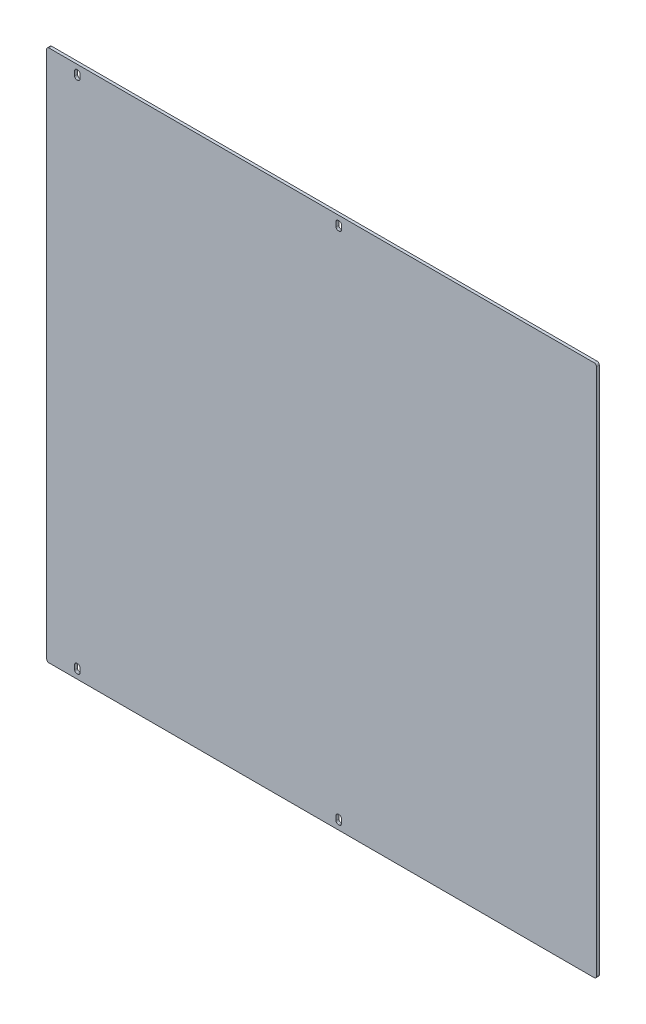
SolidWorks part; units mm, degrees
ref_plane "Front Plane" through (0, 0, 0) normal (0, 0, 1) x (1, 0, 0)
ref_plane "Top Plane" through (0, 0, 0) normal (0, 1, 0) x (1, 0, 0)
ref_plane "Right Plane" through (0, 0, 0) normal (1, 0, 0) x (0, 0, -1)
sketch "Sketch1" plane through (0, 0, 0) normal (0, 0, 1) x (1, 0, 0)
  line L1 (-224.9767, 260.7264) -> (384.6233, 260.7264)
  line L2 (-224.9767, 260.7264) -> (-224.9767, -329.6986)
  line L3 (-224.9767, -329.6986) -> (384.6233, -329.6986)
  line L4 (384.6233, 260.7264) -> (384.6233, -329.6986)
  dimension "D1" = 590.425
  dimension "D2" = 609.6
extrude "Boss-Extrude1" add sketch "Sketch1" along normal blind 3.175 contours L2 L3 L4 L1
fillet "Fillet1" radius 2.54 4 edges at (-224.9767, -329.6986, 1.5875) (384.6233, -329.6986, 1.5875) (384.6233, 260.7264, 1.5875) (-224.9767, 260.7264, 1.5875)
sketch "Sketch2" plane through (0, 0, 3.175) normal (0, 0, 1) x (1, 0, 0)
  line L0 (-190.4767, 245.6044) -> (-191.4767, 245.6044)
  line L1 (-193.9767, 248.1044) -> (-193.9767, 253.1044)
  line L2 (-190.4767, 255.6044) -> (-191.4767, 255.6044)
  line L3 (-187.9767, 248.1044) -> (-187.9767, 253.1044)
  line L4 (-190.9767, 255.6044) -> (-190.9767, 245.6044) construction
  line L5 (-193.9767, 250.6044) -> (-187.9767, 250.6044) construction
  line L6 (-205.9767, 250.6044) -> (403.6233, 250.6044) construction
  line L7 (-205.9767, 605.4044) -> (-205.9767, -288.9956) construction
  line L8 (403.6233, -288.9956) -> (403.6233, 605.4044) construction
  line L9 (98.8233, 253.1044) -> (98.8233, 248.1044) construction
  line L10 (403.6233, 253.1044) -> (-205.9767, 253.1044) construction
  line L11 (-205.9767, 248.1044) -> (403.6233, 248.1044) construction
  line L12 (99.3233, 245.6044) -> (98.3233, 245.6044)
  line L13 (95.8233, 248.1044) -> (95.8233, 253.1044)
  line L14 (99.3233, 255.6044) -> (98.3233, 255.6044)
  line L15 (-193.9767, 255.6044) -> (-187.9767, 255.6044) construction
  line L16 (-193.9767, 255.6044) -> (-193.9767, 245.6044) construction
  line L17 (-193.9767, 245.6044) -> (-187.9767, 245.6044) construction
  line L18 (-187.9767, 255.6044) -> (-187.9767, 245.6044) construction
  line L19 (-193.9767, 255.6044) -> (-187.9767, 245.6044) construction
  line L20 (-193.9767, 245.6044) -> (-187.9767, 255.6044) construction
  line L21 (101.8233, 248.1044) -> (101.8233, 253.1044)
  line L22 (98.8233, 255.6044) -> (98.8233, 245.6044) construction
  line L23 (95.8233, 250.6044) -> (101.8233, 250.6044) construction
  line L24 (95.8233, 255.6044) -> (101.8233, 255.6044) construction
  line L25 (95.8233, 255.6044) -> (95.8233, 245.6044) construction
  line L26 (95.8233, 245.6044) -> (101.8233, 245.6044) construction
  line L27 (101.8233, 255.6044) -> (101.8233, 245.6044) construction
  line L28 (95.8233, 255.6044) -> (101.8233, 245.6044) construction
  line L29 (95.8233, 245.6044) -> (101.8233, 255.6044) construction
  line L30 (389.1233, 245.6044) -> (388.1233, 245.6044)
  line L31 (385.6233, 248.1044) -> (385.6233, 253.1044)
  line L32 (389.1233, 255.6044) -> (388.1233, 255.6044)
  line L33 (391.6233, 248.1044) -> (391.6233, 253.1044)
  line L34 (388.6233, 255.6044) -> (388.6233, 245.6044) construction
  line L35 (385.6233, 250.6044) -> (391.6233, 250.6044) construction
  line L36 (385.6233, 255.6044) -> (391.6233, 255.6044) construction
  line L37 (385.6233, 255.6044) -> (385.6233, 245.6044) construction
  line L38 (385.6233, 245.6044) -> (391.6233, 245.6044) construction
  line L39 (391.6233, 255.6044) -> (391.6233, 245.6044) construction
  line L40 (385.6233, 255.6044) -> (391.6233, 245.6044) construction
  line L41 (385.6233, 245.6044) -> (391.6233, 255.6044) construction
  line L42 (-224.9767, -34.4861) -> (384.6233, -34.4861) construction
  line L43 (-224.9767, 258.1864) -> (-224.9767, -327.1586) construction
  line L44 (384.6233, 258.1864) -> (384.6233, -327.1586) construction
  line L45 (385.6233, -314.5766) -> (391.6233, -324.5766) construction
  line L46 (385.6233, -324.5766) -> (391.6233, -314.5766) construction
  line L47 (391.6233, -324.5766) -> (391.6233, -314.5766) construction
  line L48 (385.6233, -314.5766) -> (391.6233, -314.5766) construction
  line L49 (385.6233, -324.5766) -> (385.6233, -314.5766) construction
  line L50 (385.6233, -324.5766) -> (391.6233, -324.5766) construction
  line L51 (385.6233, -319.5766) -> (391.6233, -319.5766) construction
  line L52 (388.6233, -324.5766) -> (388.6233, -314.5766) construction
  line L53 (95.8233, -314.5766) -> (101.8233, -324.5766) construction
  line L54 (95.8233, -324.5766) -> (101.8233, -314.5766) construction
  line L55 (101.8233, -324.5766) -> (101.8233, -314.5766) construction
  line L56 (95.8233, -314.5766) -> (101.8233, -314.5766) construction
  line L57 (95.8233, -324.5766) -> (95.8233, -314.5766) construction
  line L58 (95.8233, -324.5766) -> (101.8233, -324.5766) construction
  line L59 (95.8233, -319.5766) -> (101.8233, -319.5766) construction
  line L60 (98.8233, -324.5766) -> (98.8233, -314.5766) construction
  line L61 (-193.9767, -314.5766) -> (-187.9767, -324.5766) construction
  line L62 (-193.9767, -324.5766) -> (-187.9767, -314.5766) construction
  line L63 (-187.9767, -324.5766) -> (-187.9767, -314.5766) construction
  line L64 (-193.9767, -314.5766) -> (-187.9767, -314.5766) construction
  line L65 (-193.9767, -324.5766) -> (-193.9767, -314.5766) construction
  line L66 (-193.9767, -324.5766) -> (-187.9767, -324.5766) construction
  line L67 (98.8233, -322.0766) -> (98.8233, -317.0766) construction
  line L68 (-205.9767, -319.5766) -> (403.6233, -319.5766) construction
  line L69 (-193.9767, -319.5766) -> (-187.9767, -319.5766) construction
  line L70 (-190.9767, -324.5766) -> (-190.9767, -314.5766) construction
  line L71 (391.6233, -317.0766) -> (391.6233, -322.0766)
  line L72 (389.1233, -324.5766) -> (388.1233, -324.5766)
  line L73 (385.6233, -317.0766) -> (385.6233, -322.0766)
  line L74 (389.1233, -314.5766) -> (388.1233, -314.5766)
  line L75 (101.8233, -317.0766) -> (101.8233, -322.0766)
  line L76 (99.3233, -324.5766) -> (98.3233, -324.5766)
  line L77 (95.8233, -317.0766) -> (95.8233, -322.0766)
  line L78 (99.3233, -314.5766) -> (98.3233, -314.5766)
  line L79 (-187.9767, -317.0766) -> (-187.9767, -322.0766)
  line L80 (-190.4767, -324.5766) -> (-191.4767, -324.5766)
  line L81 (-193.9767, -317.0766) -> (-193.9767, -322.0766)
  line L82 (-190.4767, -314.5766) -> (-191.4767, -314.5766)
  arc A0 (-191.4767, 245.6044) -> (-193.9767, 248.1044) centre (-191.4767, 248.1044) cw
  arc A1 (-191.4767, 255.6044) -> (-193.9767, 253.1044) centre (-191.4767, 253.1044) ccw
  arc A2 (-187.9767, 253.1044) -> (-190.4767, 255.6044) centre (-190.4767, 253.1044) ccw
  arc A3 (-190.4767, 245.6044) -> (-187.9767, 248.1044) centre (-190.4767, 248.1044) ccw
  arc A4 (98.3233, 245.6044) -> (95.8233, 248.1044) centre (98.3233, 248.1044) cw
  arc A5 (98.3233, 255.6044) -> (95.8233, 253.1044) centre (98.3233, 253.1044) ccw
  arc A6 (101.8233, 253.1044) -> (99.3233, 255.6044) centre (99.3233, 253.1044) ccw
  arc A7 (99.3233, 245.6044) -> (101.8233, 248.1044) centre (99.3233, 248.1044) ccw
  arc A8 (388.1233, 245.6044) -> (385.6233, 248.1044) centre (388.1233, 248.1044) cw
  arc A9 (388.1233, 255.6044) -> (385.6233, 253.1044) centre (388.1233, 253.1044) ccw
  arc A10 (391.6233, 253.1044) -> (389.1233, 255.6044) centre (389.1233, 253.1044) ccw
  arc A11 (389.1233, 245.6044) -> (391.6233, 248.1044) centre (389.1233, 248.1044) ccw
  arc A12 (389.1233, -314.5766) -> (391.6233, -317.0766) centre (389.1233, -317.0766) cw
  arc A13 (391.6233, -322.0766) -> (389.1233, -324.5766) centre (389.1233, -322.0766) cw
  arc A14 (388.1233, -324.5766) -> (385.6233, -322.0766) centre (388.1233, -322.0766) cw
  arc A15 (388.1233, -314.5766) -> (385.6233, -317.0766) centre (388.1233, -317.0766) ccw
  arc A16 (99.3233, -314.5766) -> (101.8233, -317.0766) centre (99.3233, -317.0766) cw
  arc A17 (101.8233, -322.0766) -> (99.3233, -324.5766) centre (99.3233, -322.0766) cw
  arc A18 (98.3233, -324.5766) -> (95.8233, -322.0766) centre (98.3233, -322.0766) cw
  arc A19 (98.3233, -314.5766) -> (95.8233, -317.0766) centre (98.3233, -317.0766) ccw
  arc A20 (-190.4767, -314.5766) -> (-187.9767, -317.0766) centre (-190.4767, -317.0766) cw
  arc A21 (-187.9767, -322.0766) -> (-190.4767, -324.5766) centre (-190.4767, -322.0766) cw
  arc A22 (-191.4767, -324.5766) -> (-193.9767, -322.0766) centre (-191.4767, -322.0766) cw
  arc A23 (-191.4767, -314.5766) -> (-193.9767, -317.0766) centre (-191.4767, -317.0766) ccw
  point P28 (98.8233, 250.6044)
  point P29 (-190.9767, 250.6044)
  point P32 (-190.9767, 250.6044)
  point P53 (98.8233, 250.6044)
  point P74 (388.6233, 250.6044)
  point P147 (388.6233, -319.5766)
  point P148 (98.8233, -319.5766)
  point P149 (-190.9767, -319.5766)
  dimension "D1" = 2.5
  dimension "D2" = 3
  dimension "D3" = 6
  dimension "D4" = 15
  dimension "D5" = 10
  dimension "D6" = 15
extrude "Cut-Extrude1" cut sketch "Sketch2" against normal up to surface (3.175 mm away) up to face at (79.8233, -34.4861, 0)
